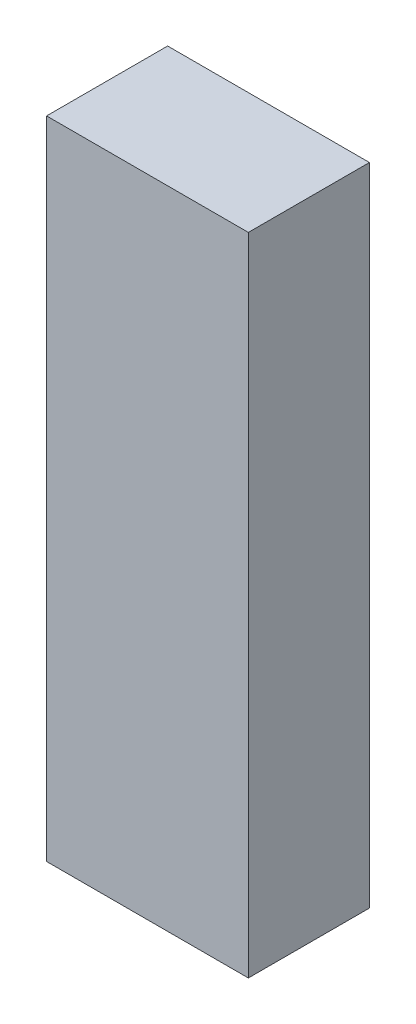
SolidWorks part; units mm, degrees
ref_plane "Front Plane" through (0, 0, 0) normal (0, 0, 1) x (1, 0, 0)
ref_plane "Top Plane" through (0, 0, 0) normal (0, 1, 0) x (1, 0, 0)
ref_plane "Right Plane" through (0, 0, 0) normal (1, 0, 0) x (0, 0, -1)
sketch "Sketch1" plane through (0, 0, 0) normal (0, 0, 1) x (1, 0, 0)
  line L1 (0, 0) -> (12.7, 0)
  line L2 (0, 0) -> (0, 40.64)
  line L3 (0, 40.64) -> (12.7, 40.64)
  line L4 (12.7, 0) -> (12.7, 40.64)
  dimension "D1" = 40.64
  dimension "D2" = 12.7
extrude "Boss-Extrude1" add sketch "Sketch1" along normal blind 7.62
equation "\"Foamcore\" = .1in"
equation "\"MDF\" = .3in"
equation "\"Gmaterial\"= \"MDF\""
equation "\"D1@Boss-Extrude1\"=\"Gmaterial\""
equation "\"D1@Sketch1\"=1+2*\"Gmaterial\""
